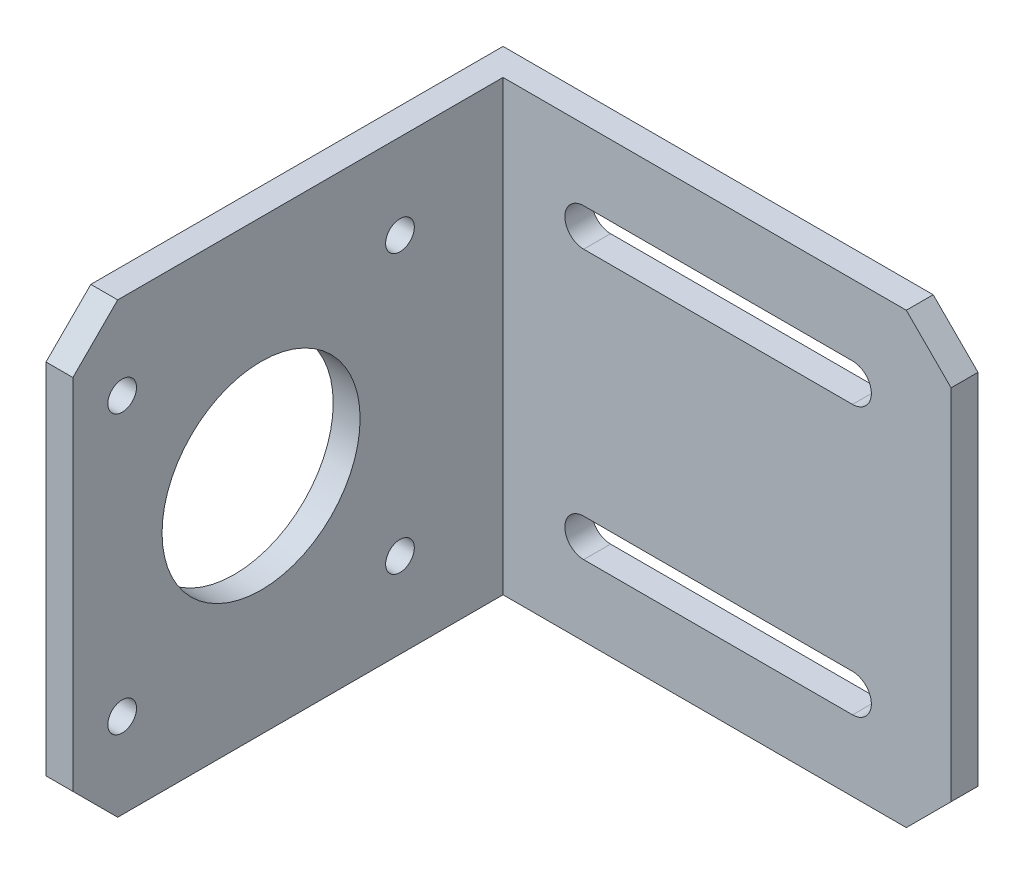
SolidWorks part; units mm, degrees
ref_plane "前视基准面" through (0, 0, 0) normal (0, 0, 1) x (1, 0, 0)
ref_plane "上视基准面" through (0, 0, 0) normal (0, 1, 0) x (1, 0, 0)
ref_plane "右视基准面" through (0, 0, 0) normal (1, 0, 0) x (0, 0, -1)
sketch "草图1" plane through (0, 0, 0) normal (0, 0, 1) x (1, 0, 0)
  line L0 (0, 25) -> (53, 25) construction
  line L1 (0, 0) -> (53, 0)
  line L2 (0, 0) -> (0, 50)
  line L3 (0, 50) -> (53, 50)
  line L4 (53, 0) -> (53, 50)
  line L5 (12, 40) -> (42, 40) construction
  line L6 (12, 42.1) -> (42, 42.1)
  line L7 (12, 37.9) -> (42, 37.9)
  line L8 (12, 10) -> (42, 10) construction
  line L9 (12, 7.9) -> (42, 7.9)
  line L10 (12, 12.1) -> (42, 12.1)
  arc A0 (12, 42.1) -> (12, 37.9) centre (12, 40) ccw
  arc A1 (42, 37.9) -> (42, 42.1) centre (42, 40) ccw
  arc A2 (12, 7.9) -> (12, 12.1) centre (12, 10) cw
  arc A3 (42, 12.1) -> (42, 7.9) centre (42, 10) cw
  point P9 (27, 40)
  point P16 (27, 10)
  dimension "D1" = 50
  dimension "D2" = 53
  dimension "D3" = 15
  dimension "D4" = 30
  dimension "D5" = 11
  dimension "D6" = 4.2
extrude "凸台-拉伸1" add sketch "草图1" along normal blind 3
sketch "草图2" plane through (0, 0, 0) normal (-1, 0, 0) x (0, 0, 1)
  line L0 (3, 0) -> (0, 0) construction
  line L1 (0, 50) -> (51, 50)
  line L2 (0, 50) -> (0, 0)
  line L3 (0, 0) -> (51, 0)
  line L4 (51, 50) -> (51, 0)
  line L5 (0, 25) -> (51, 25) construction
  circle A0 centre (30, 25) radius 11.05
  circle A1 centre (45.5, 40.5) radius 1.6
  circle A2 centre (45.5, 9.5) radius 1.6
  circle A3 centre (14.5, 9.5) radius 1.6
  circle A4 centre (14.5, 40.5) radius 1.6
  point P22 (30, 25)
  dimension "D2" = 22.1
  dimension "D5" = 3.2
  dimension "D1" = 51
  dimension "D3" = 21
  dimension "D4" = 15.5
  dimension "D6" = 15.5
  dimension "D8" = 90
  dimension "D9" = 21.9203
  dimension "D7" = 4
extrude "凸台-拉伸2" add sketch "草图2" against normal blind 3
chamfer "倒角1" distance 5 angle 45 4 edges at (53, 50, 1.5) (53, 0, 1.5) (1.5, 0, 51) (1.5, 50, 51)
